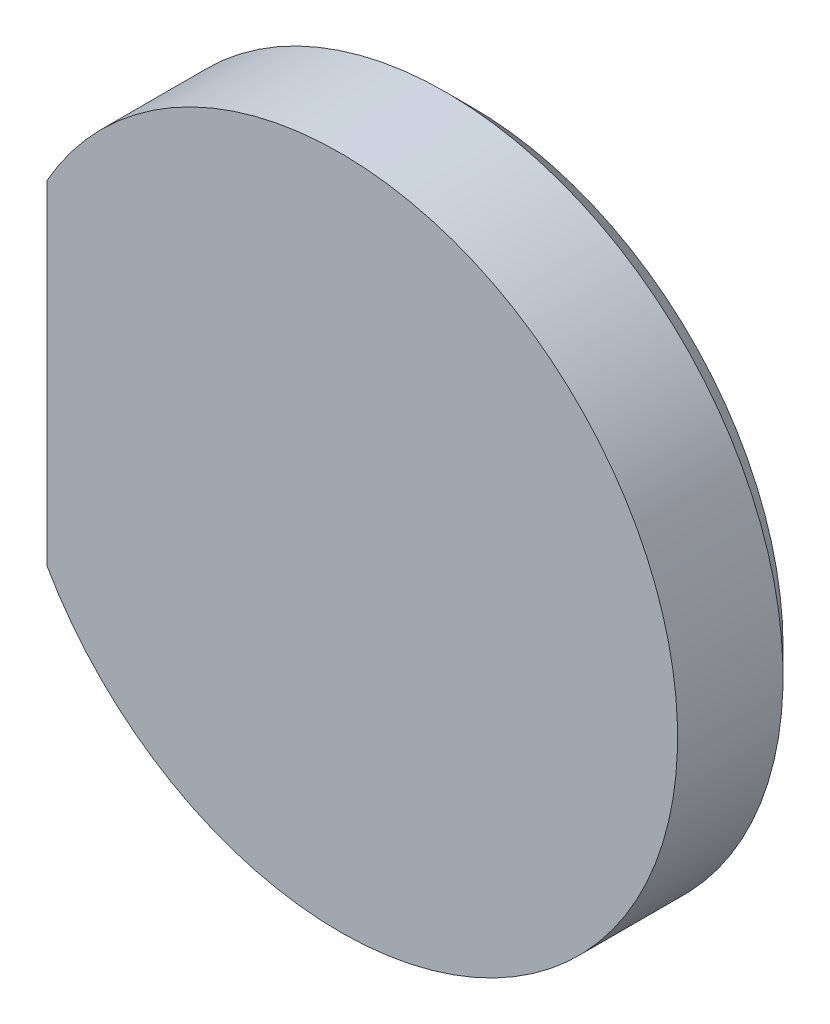
SolidWorks part; units mm, degrees
material "Сплав 2024"
ref_plane "Спереди" through (0, 0, 0) normal (0, 0, 1) x (1, 0, 0)
ref_plane "Сверху" through (0, 0, 0) normal (0, 1, 0) x (1, 0, 0)
ref_plane "Справа" through (0, 0, 0) normal (1, 0, 0) x (0, 0, -1)
sketch "Эскиз1" plane through (0, 0, 0) normal (0, 0, 1) x (1, 0, 0)
  circle A0 centre (0, 0) radius 25.6
  dimension "D1" = 51.2
extrude "Бобышка-Вытянуть1" add sketch "Эскиз1" along normal blind 10
chamfer "Фаска1" distance 2 angle 45 1 edges at (25.6, 0, 0)
sketch "Эскиз2" plane through (0, 0, 10) normal (0, 0, 1) x (1, 0, 0)
  line L0 (-22.25, -12.6609) -> (-22.25, 12.6609)
  line L1 (-22.25, -12.5) -> (-22.25, -10) construction
  circle A0 centre (0, 0) radius 25.6 construction
  arc A1 (-22.25, 12.6609) -> (-22.25, -12.6609) centre (0, 0) ccw
  circle A2 centre (0, 0) radius 25.6 construction
extrude "Вырез-Вытянуть1" cut sketch "Эскиз2" against normal blind 2.5
sketch "Эскиз3" plane through (0, 0, 0) normal (0, 0, -1) x (-1, 0, 0)
  circle A0 centre (0, 0) radius 23.2
  dimension "D1" = 46.4
extrude "Вырез-Вытянуть2" cut sketch "Эскиз3" against normal offset from surface (7.5 mm away) 2.5 up to face at (1.675, 0, 10)
ref_plane "Плоскость1" through (0, -12.6609, 0) normal (0, 1, 0) x (1, 0, 0)
sketch "Эскиз5" plane through (0, 0, 0) normal (0, 0, -1) x (-1, 0, 0)
  line L0 (22.25, 6.571) -> (22.25, -6.571) construction
  line L1 (17.5672, 12.6609) -> (26.9328, 12.6609)
  line L2 (17.5672, 12.6609) -> (17.5672, -12.6609)
  line L3 (17.5672, -12.6609) -> (26.9328, -12.6609)
  line L4 (26.9328, 12.6609) -> (26.9328, -12.6609)
  line L5 (17.5672, 12.6609) -> (26.9328, -12.6609) construction
  line L6 (17.5672, -12.6609) -> (26.9328, 12.6609) construction
  line L7 (1.375, -12.6609) -> (-1.375, -12.6609) construction
  point P0 (22.25, 0)
extrude "Вырез-Вытянуть3" cut sketch "Эскиз5" against normal up to surface (7.5 mm away) up to face at (0.475, 0, 7.5)
fillet "Скругление2" radius 4 2 edges at (-19.4407, 12.6609, 3.75) (-19.4407, -12.6609, 3.75)
